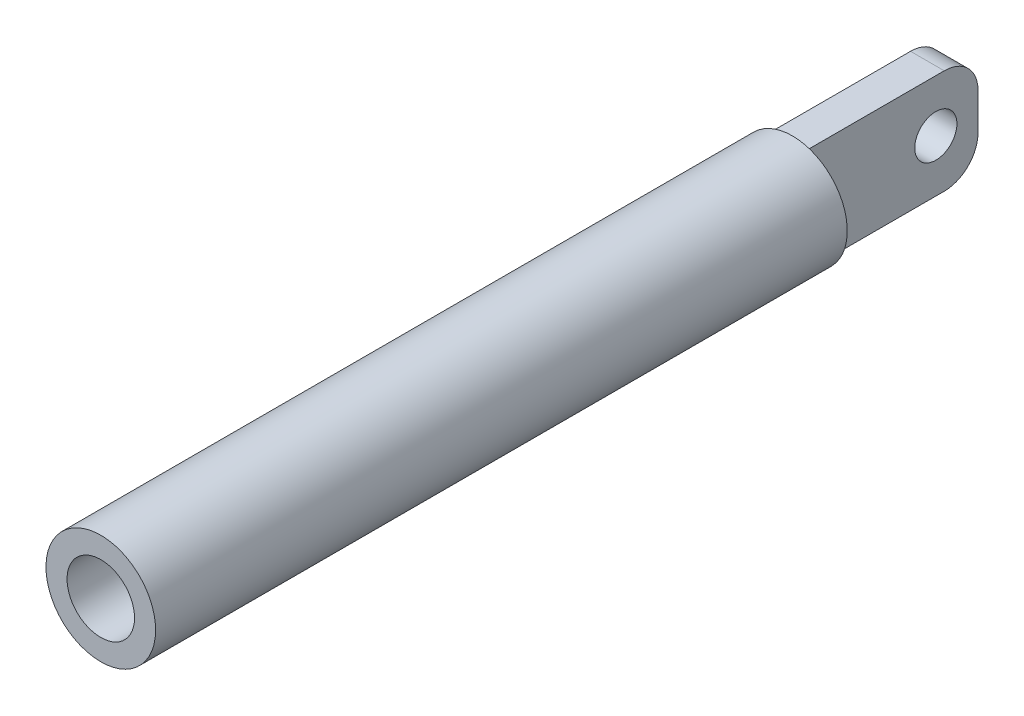
SolidWorks part; units mm, degrees
material "Thornel Mat VMA"
ref_plane "Front Plane" through (0, 0, 0) normal (0, 0, 1) x (1, 0, 0)
ref_plane "Top Plane" through (0, 0, 0) normal (0, 1, 0) x (1, 0, 0)
ref_plane "Right Plane" through (0, 0, 0) normal (1, 0, 0) x (0, 0, -1)
sketch "Sketch1" plane through (0, 0, 0) normal (0, 0, 1) x (1, 0, 0)
  circle A0 centre (0, 0) radius 6.5
  circle A1 centre (0, 0) radius 4
  dimension "D1" = 13
  dimension "D2" = 8
extrude "Boss-Extrude1" add sketch "Sketch1" along normal blind 20
sketch "Sketch2" plane through (0, 0, 0) normal (0, 0, -1) x (-1, 0, 0)
  circle A0 centre (0, 0) radius 6.5
  circle A1 centre (0, 0) radius 6.5 construction
extrude "Boss-Extrude2" add sketch "Sketch2" along normal blind 62
sketch "Sketch3" plane through (0, 0, -62) normal (0, 0, -1) x (-1, 0, 0)
  line L1 (-2, -6.1847) -> (2, -6.1847)
  line L2 (-2, -6.1847) -> (-2, 6.1847)
  line L3 (-2, 6.1847) -> (2, 6.1847)
  line L4 (2, -6.1847) -> (2, 6.1847)
  line L5 (-2, -6.1847) -> (2, 6.1847) construction
  line L6 (-2, 6.1847) -> (2, -6.1847) construction
  circle A0 centre (0, 0) radius 6.5 construction
  point P0 (0, 0)
  dimension "D1" = 4
extrude "Boss-Extrude3" add sketch "Sketch3" along normal blind 20
sketch "Sketch4" plane through (2, 0, 0) normal (1, 0, 0) x (0, 0, -1)
  line L0 (82, 6.1847) -> (82, -6.1847) construction
  circle A0 centre (77, 0) radius 2.5
  dimension "D2" = 5
  dimension "D1" = 5
fillet "Fillet1" radius 4 2 edges at (0, -6.1847, -82) (0, 6.1847, -82)
extrude "Cut-Extrude1" cut sketch "Sketch4" against normal up to surface (4 mm away) up to face at (-2, 0, -74.2761)
